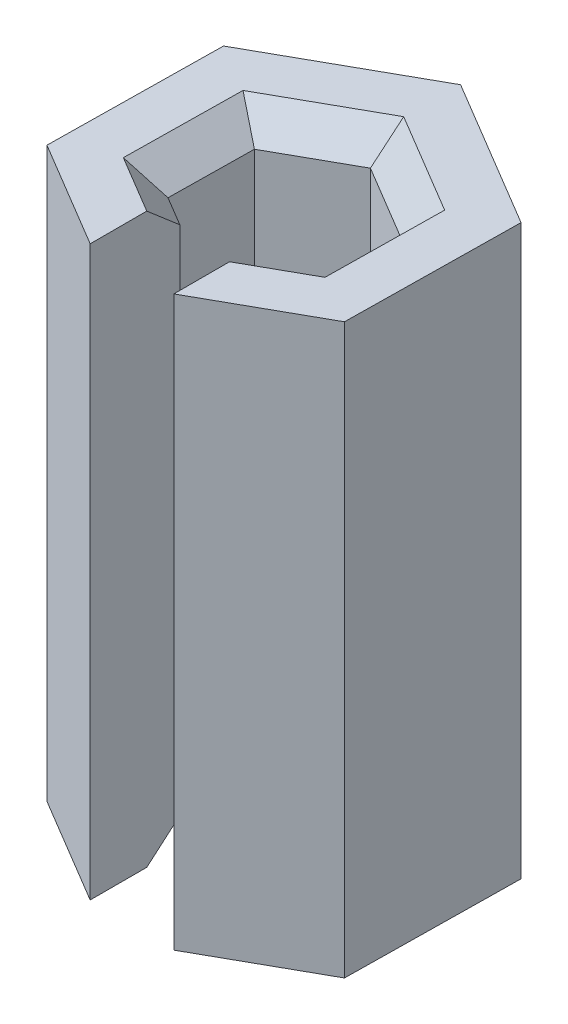
SolidWorks part; units mm, degrees
ref_plane "Front Plane" through (0, 0, 0) normal (0, 0, 1) x (1, 0, 0)
ref_plane "Top Plane" through (0, 0, 0) normal (0, 1, 0) x (1, 0, 0)
ref_plane "Right Plane" through (0, 0, 0) normal (1, 0, 0) x (0, 0, -1)
sketch "Sketch1" plane through (0, 0, 0) normal (0, 1, 0) x (1, 0, 0)
  line L1 (0.0415, 2.9997) -> (-2.5771, 1.5358)
  line L2 (-2.5771, 1.5358) -> (-2.6186, -1.4639)
  line L3 (-2.6186, -1.4639) -> (-0.0415, -2.9997)
  line L4 (-0.0415, -2.9997) -> (2.5771, -1.5358)
  line L5 (2.5771, -1.5358) -> (2.6186, 1.4639)
  line L6 (2.6186, 1.4639) -> (0.0415, 2.9997)
  line L7 (0.0849, 6.13) -> (-5.2663, 3.1385)
  line L8 (-5.2663, 3.1385) -> (-5.3512, -2.9915)
  line L9 (-5.3512, -2.9915) -> (-0.0849, -6.13)
  line L10 (-0.0849, -6.13) -> (5.2663, -3.1385)
  line L11 (5.2663, -3.1385) -> (5.3512, 2.9915)
  line L12 (5.3512, 2.9915) -> (0.0849, 6.13)
  circle A0 centre (0, 0) radius 2.5981 construction
  circle A1 centre (0, 0) radius 5.3092 construction
  dimension "D1" = 6
extrude "Boss-Extrude1" add sketch "Sketch1" along normal blind 20
chamfer "Chamfer1" distance 1 angle 45 12 edges at (-2.5978, 20, -0.036) (-1.3301, 20, 2.2318) (1.2678, 20, 2.2678) (2.5978, 20, 0.036) (1.3301, 20, -2.2318) (-1.2678, 20, -2.2678) (1.3301, 0, -2.2318) (-1.2678, 0, -2.2678) (-2.5978, 0, -0.036) (-1.3301, 0, 2.2318) (1.2678, 0, 2.2678) (2.5978, 0, 0.036)
sketch "Sketch2" plane through (0, 20, 0) normal (0, 1, 0) x (1, 0, 0)
  line L1 (-1.5849, -1.657) -> (1.4151, -1.657)
  line L2 (-1.5849, -1.657) -> (-1.5849, -7.1768)
  line L3 (-1.5849, -7.1768) -> (1.4151, -7.1768)
  line L4 (1.4151, -1.657) -> (1.4151, -7.1768)
  dimension "D1" = 1.5
  dimension "D2" = 3
extrude "Cut-Extrude1" cut sketch "Sketch2" against normal blind 26
